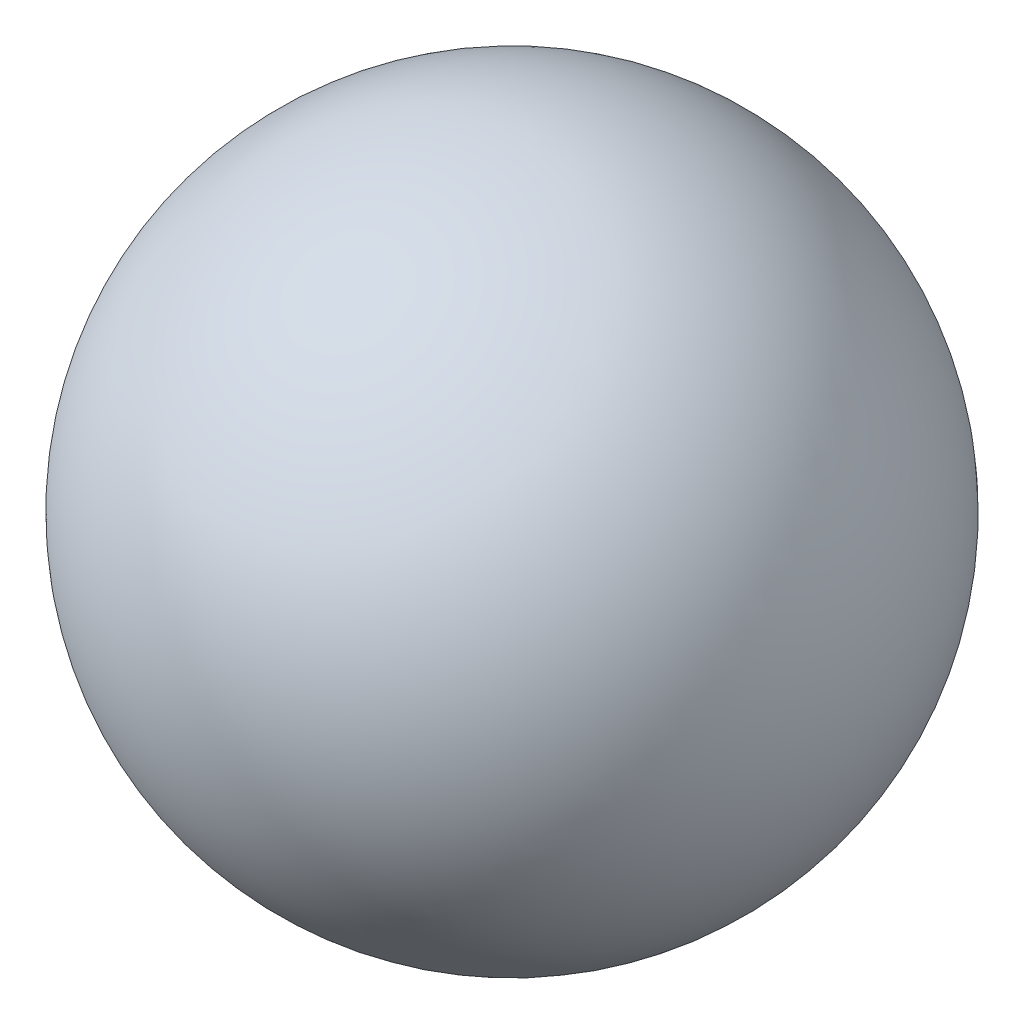
SolidWorks part; units mm, degrees
ref_plane "Front" through (0, 0, 0) normal (0, 0, 1) x (1, 0, 0)
ref_plane "Top" through (0, 0, 0) normal (0, 1, 0) x (1, 0, 0)
ref_plane "Right" through (0, 0, 0) normal (1, 0, 0) x (0, 0, -1)
sketch "Sketch3" plane through (0, 0, 0) normal (0, 1, 0) x (1, 0, 0)
  line L0 (-156.9464, -199.7094) -> (0, 0) construction
  line L1 (0, 0) -> (-156.9464, -199.7094)
  arc A0 (0, 0) -> (-156.9464, -199.7094) centre (-78.4732, -99.8547) ccw
  dimension "D1" = 127
revolve "Revolve1" add sketch "Sketch3" angle 360 about L0
